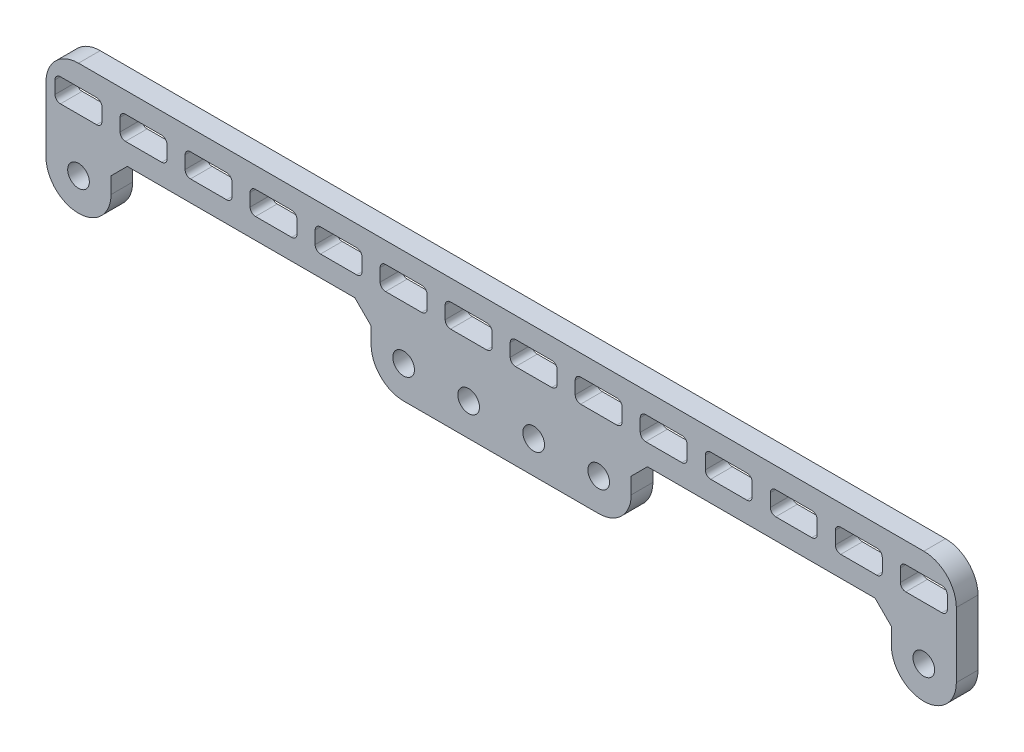
SolidWorks part; units mm, degrees
ref_plane "Alzado" through (0, 0, 0) normal (0, 0, 1) x (1, 0, 0)
ref_plane "Planta" through (0, 0, 0) normal (0, 1, 0) x (1, 0, 0)
ref_plane "Vista lateral" through (0, 0, 0) normal (1, 0, 0) x (0, 0, -1)
sketch "Model" plane through (0, 0, 0) normal (0, 0, 1) x (1, 0, 0)
  line L0 (238.4291, 228.7422) -> (355.4291, 228.7422)
  line L1 (359.9291, 224.2422) -> (359.9291, 215.2422)
  line L2 (321.9291, 222.6172) -> (316.9291, 222.6172)
  line L3 (316.1791, 223.3672) -> (316.1791, 225.1172)
  line L4 (316.9291, 225.8672) -> (321.9291, 225.8672)
  line L5 (322.6791, 225.1172) -> (322.6791, 223.3672)
  line L6 (357.9291, 222.6172) -> (352.9291, 222.6172)
  line L7 (352.1791, 223.3672) -> (352.1791, 225.1172)
  line L8 (352.9291, 225.8672) -> (357.9291, 225.8672)
  line L9 (358.6791, 225.1172) -> (358.6791, 223.3672)
  line L10 (348.9291, 222.6172) -> (343.9291, 222.6172)
  line L11 (343.1791, 223.3672) -> (343.1791, 225.1172)
  line L12 (343.9291, 225.8672) -> (348.9291, 225.8672)
  line L13 (349.6791, 225.1172) -> (349.6791, 223.3672)
  line L14 (339.9291, 222.6172) -> (334.9291, 222.6172)
  line L15 (334.1791, 223.3672) -> (334.1791, 225.1172)
  line L16 (334.9291, 225.8672) -> (339.9291, 225.8672)
  line L17 (340.6791, 225.1172) -> (340.6791, 223.3672)
  line L18 (330.9291, 222.6172) -> (325.9291, 222.6172)
  line L19 (325.1791, 223.3672) -> (325.1791, 225.1172)
  line L20 (325.9291, 225.8672) -> (330.9291, 225.8672)
  line L21 (331.6791, 225.1172) -> (331.6791, 223.3672)
  line L22 (317.1791, 219.7422) -> (348.6791, 219.7422)
  line L23 (314.9291, 215.2422) -> (314.9291, 217.4922)
  line L24 (350.9291, 215.2422) -> (350.9291, 217.4922)
  line L25 (350.9291, 217.4922) -> (348.6791, 219.7422)
  line L26 (314.9291, 217.4922) -> (317.1791, 219.7422)
  line L27 (233.9291, 224.2422) -> (233.9291, 215.2422)
  line L28 (271.9291, 222.6172) -> (276.9291, 222.6172)
  line L29 (277.6791, 223.3672) -> (277.6791, 225.1172)
  line L30 (276.9291, 225.8672) -> (271.9291, 225.8672)
  line L31 (271.1791, 225.1172) -> (271.1791, 223.3672)
  line L32 (235.9291, 222.6172) -> (240.9291, 222.6172)
  line L33 (241.6791, 223.3672) -> (241.6791, 225.1172)
  line L34 (240.9291, 225.8672) -> (235.9291, 225.8672)
  line L35 (235.1791, 225.1172) -> (235.1791, 223.3672)
  line L36 (244.9291, 222.6172) -> (249.9291, 222.6172)
  line L37 (250.6791, 223.3672) -> (250.6791, 225.1172)
  line L38 (249.9291, 225.8672) -> (244.9291, 225.8672)
  line L39 (244.1791, 225.1172) -> (244.1791, 223.3672)
  line L40 (253.9291, 222.6172) -> (258.9291, 222.6172)
  line L41 (259.6791, 223.3672) -> (259.6791, 225.1172)
  line L42 (258.9291, 225.8672) -> (253.9291, 225.8672)
  line L43 (253.1791, 225.1172) -> (253.1791, 223.3672)
  line L44 (262.9291, 222.6172) -> (267.9291, 222.6172)
  line L45 (268.6791, 223.3672) -> (268.6791, 225.1172)
  line L46 (267.9291, 225.8672) -> (262.9291, 225.8672)
  line L47 (262.1791, 225.1172) -> (262.1791, 223.3672)
  line L48 (276.6791, 219.7422) -> (245.1791, 219.7422)
  line L49 (278.9291, 215.2422) -> (278.9291, 217.4922)
  line L50 (242.9291, 215.2422) -> (242.9291, 217.4922)
  line L51 (242.9291, 217.4922) -> (245.1791, 219.7422)
  line L52 (278.9291, 217.4922) -> (276.6791, 219.7422)
  line L53 (283.4291, 210.7422) -> (310.4291, 210.7422)
  line L54 (307.9291, 222.6172) -> (312.9291, 222.6172)
  line L55 (313.6791, 223.3672) -> (313.6791, 225.1172)
  line L56 (312.9291, 225.8672) -> (307.9291, 225.8672)
  line L57 (307.1791, 225.1172) -> (307.1791, 223.3672)
  line L58 (280.9291, 222.6172) -> (285.9291, 222.6172)
  line L59 (286.6791, 223.3672) -> (286.6791, 225.1172)
  line L60 (285.9291, 225.8672) -> (280.9291, 225.8672)
  line L61 (280.1791, 225.1172) -> (280.1791, 223.3672)
  line L62 (289.9291, 222.6172) -> (294.9291, 222.6172)
  line L63 (295.6791, 223.3672) -> (295.6791, 225.1172)
  line L64 (294.9291, 225.8672) -> (289.9291, 225.8672)
  line L65 (289.1791, 225.1172) -> (289.1791, 223.3672)
  line L66 (298.9291, 222.6172) -> (303.9291, 222.6172)
  line L67 (304.6791, 223.3672) -> (304.6791, 225.1172)
  line L68 (303.9291, 225.8672) -> (298.9291, 225.8672)
  line L69 (298.1791, 225.1172) -> (298.1791, 223.3672)
  arc A0 (359.9291, 224.2422) -> (355.4291, 228.7422) centre (355.4291, 224.2422) ccw
  circle A1 centre (283.4291, 215.2422) radius 1.5
  circle A2 centre (355.4291, 215.2422) radius 1.5
  arc A3 (316.1791, 223.3672) -> (316.9291, 222.6172) centre (316.9291, 223.3672) ccw
  arc A4 (316.9291, 225.8672) -> (316.1791, 225.1172) centre (316.9291, 225.1172) ccw
  arc A5 (322.6791, 225.1172) -> (321.9291, 225.8672) centre (321.9291, 225.1172) ccw
  arc A6 (321.9291, 222.6172) -> (322.6791, 223.3672) centre (321.9291, 223.3672) ccw
  arc A7 (352.1791, 223.3672) -> (352.9291, 222.6172) centre (352.9291, 223.3672) ccw
  arc A8 (352.9291, 225.8672) -> (352.1791, 225.1172) centre (352.9291, 225.1172) ccw
  arc A9 (358.6791, 225.1172) -> (357.9291, 225.8672) centre (357.9291, 225.1172) ccw
  arc A10 (357.9291, 222.6172) -> (358.6791, 223.3672) centre (357.9291, 223.3672) ccw
  arc A11 (343.1791, 223.3672) -> (343.9291, 222.6172) centre (343.9291, 223.3672) ccw
  arc A12 (343.9291, 225.8672) -> (343.1791, 225.1172) centre (343.9291, 225.1172) ccw
  arc A13 (349.6791, 225.1172) -> (348.9291, 225.8672) centre (348.9291, 225.1172) ccw
  arc A14 (348.9291, 222.6172) -> (349.6791, 223.3672) centre (348.9291, 223.3672) ccw
  arc A15 (334.1791, 223.3672) -> (334.9291, 222.6172) centre (334.9291, 223.3672) ccw
  arc A16 (334.9291, 225.8672) -> (334.1791, 225.1172) centre (334.9291, 225.1172) ccw
  arc A17 (340.6791, 225.1172) -> (339.9291, 225.8672) centre (339.9291, 225.1172) ccw
  arc A18 (339.9291, 222.6172) -> (340.6791, 223.3672) centre (339.9291, 223.3672) ccw
  arc A19 (325.1791, 223.3672) -> (325.9291, 222.6172) centre (325.9291, 223.3672) ccw
  arc A20 (325.9291, 225.8672) -> (325.1791, 225.1172) centre (325.9291, 225.1172) ccw
  arc A21 (331.6791, 225.1172) -> (330.9291, 225.8672) centre (330.9291, 225.1172) ccw
  arc A22 (330.9291, 222.6172) -> (331.6791, 223.3672) centre (330.9291, 223.3672) ccw
  arc A23 (310.4291, 210.7422) -> (314.9291, 215.2422) centre (310.4291, 215.2422) ccw
  arc A24 (350.9291, 215.2422) -> (359.9291, 215.2422) centre (355.4291, 215.2422) ccw
  arc A25 (238.4291, 228.7422) -> (233.9291, 224.2422) centre (238.4291, 224.2422) ccw
  circle A26 centre (238.4291, 215.2422) radius 1.5
  arc A27 (276.9291, 222.6172) -> (277.6791, 223.3672) centre (276.9291, 223.3672) ccw
  arc A28 (277.6791, 225.1172) -> (276.9291, 225.8672) centre (276.9291, 225.1172) ccw
  arc A29 (271.9291, 225.8672) -> (271.1791, 225.1172) centre (271.9291, 225.1172) ccw
  arc A30 (271.1791, 223.3672) -> (271.9291, 222.6172) centre (271.9291, 223.3672) ccw
  arc A31 (240.9291, 222.6172) -> (241.6791, 223.3672) centre (240.9291, 223.3672) ccw
  arc A32 (241.6791, 225.1172) -> (240.9291, 225.8672) centre (240.9291, 225.1172) ccw
  arc A33 (235.9291, 225.8672) -> (235.1791, 225.1172) centre (235.9291, 225.1172) ccw
  arc A34 (235.1791, 223.3672) -> (235.9291, 222.6172) centre (235.9291, 223.3672) ccw
  arc A35 (249.9291, 222.6172) -> (250.6791, 223.3672) centre (249.9291, 223.3672) ccw
  arc A36 (250.6791, 225.1172) -> (249.9291, 225.8672) centre (249.9291, 225.1172) ccw
  arc A37 (244.9291, 225.8672) -> (244.1791, 225.1172) centre (244.9291, 225.1172) ccw
  arc A38 (244.1791, 223.3672) -> (244.9291, 222.6172) centre (244.9291, 223.3672) ccw
  arc A39 (258.9291, 222.6172) -> (259.6791, 223.3672) centre (258.9291, 223.3672) ccw
  arc A40 (259.6791, 225.1172) -> (258.9291, 225.8672) centre (258.9291, 225.1172) ccw
  arc A41 (253.9291, 225.8672) -> (253.1791, 225.1172) centre (253.9291, 225.1172) ccw
  arc A42 (253.1791, 223.3672) -> (253.9291, 222.6172) centre (253.9291, 223.3672) ccw
  arc A43 (267.9291, 222.6172) -> (268.6791, 223.3672) centre (267.9291, 223.3672) ccw
  arc A44 (268.6791, 225.1172) -> (267.9291, 225.8672) centre (267.9291, 225.1172) ccw
  arc A45 (262.9291, 225.8672) -> (262.1791, 225.1172) centre (262.9291, 225.1172) ccw
  arc A46 (262.1791, 223.3672) -> (262.9291, 222.6172) centre (262.9291, 223.3672) ccw
  arc A47 (278.9291, 215.2422) -> (283.4291, 210.7422) centre (283.4291, 215.2422) ccw
  arc A48 (233.9291, 215.2422) -> (242.9291, 215.2422) centre (238.4291, 215.2422) ccw
  circle A49 centre (310.4291, 215.2422) radius 1.5
  arc A50 (312.9291, 222.6172) -> (313.6791, 223.3672) centre (312.9291, 223.3672) ccw
  arc A51 (313.6791, 225.1172) -> (312.9291, 225.8672) centre (312.9291, 225.1172) ccw
  arc A52 (307.9291, 225.8672) -> (307.1791, 225.1172) centre (307.9291, 225.1172) ccw
  arc A53 (307.1791, 223.3672) -> (307.9291, 222.6172) centre (307.9291, 223.3672) ccw
  arc A54 (285.9291, 222.6172) -> (286.6791, 223.3672) centre (285.9291, 223.3672) ccw
  arc A55 (286.6791, 225.1172) -> (285.9291, 225.8672) centre (285.9291, 225.1172) ccw
  arc A56 (280.9291, 225.8672) -> (280.1791, 225.1172) centre (280.9291, 225.1172) ccw
  arc A57 (280.1791, 223.3672) -> (280.9291, 222.6172) centre (280.9291, 223.3672) ccw
  circle A58 centre (292.4291, 215.2422) radius 1.5
  arc A59 (294.9291, 222.6172) -> (295.6791, 223.3672) centre (294.9291, 223.3672) ccw
  arc A60 (295.6791, 225.1172) -> (294.9291, 225.8672) centre (294.9291, 225.1172) ccw
  arc A61 (289.9291, 225.8672) -> (289.1791, 225.1172) centre (289.9291, 225.1172) ccw
  arc A62 (289.1791, 223.3672) -> (289.9291, 222.6172) centre (289.9291, 223.3672) ccw
  circle A63 centre (301.4291, 215.2422) radius 1.5
  arc A64 (303.9291, 222.6172) -> (304.6791, 223.3672) centre (303.9291, 223.3672) ccw
  arc A65 (304.6791, 225.1172) -> (303.9291, 225.8672) centre (303.9291, 225.1172) ccw
  arc A66 (298.9291, 225.8672) -> (298.1791, 225.1172) centre (298.9291, 225.1172) ccw
  arc A67 (298.1791, 223.3672) -> (298.9291, 222.6172) centre (298.9291, 223.3672) ccw
extrude "Saliente-Extruir1" add sketch "Model" along normal blind 3
